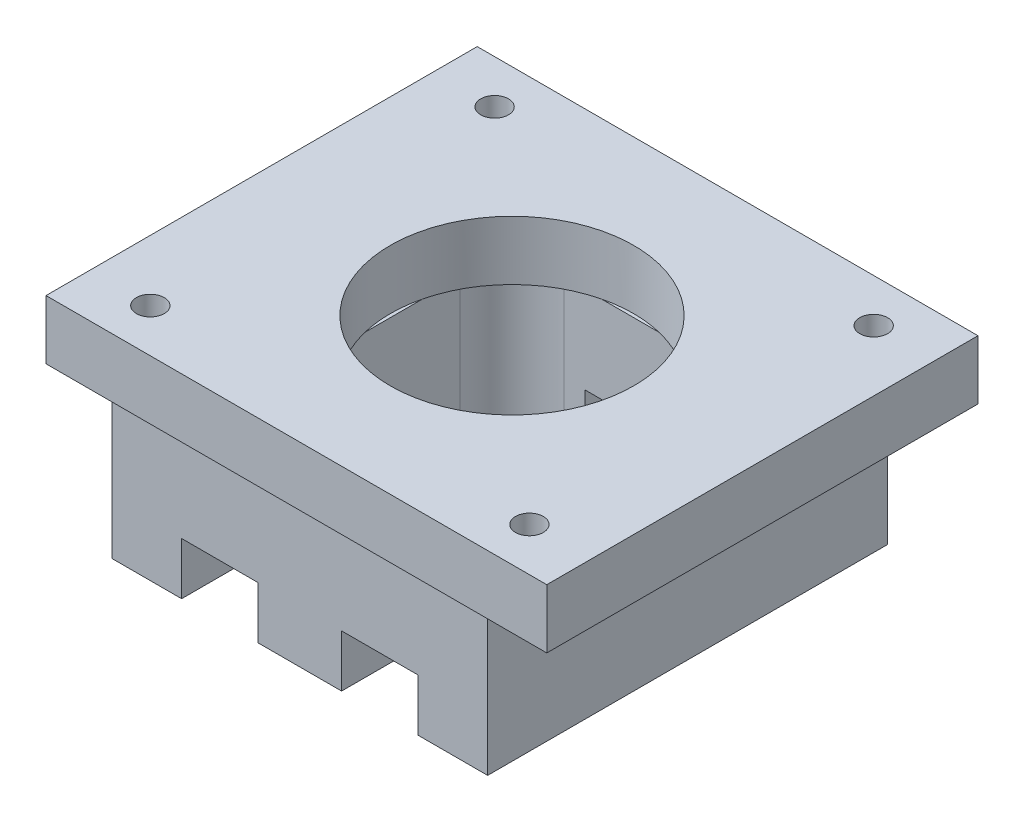
SolidWorks part; units mm, degrees
ref_plane "前视基准面" through (0, 0, 0) normal (0, 0, 1) x (1, 0, 0)
ref_plane "上视基准面" through (0, 0, 0) normal (0, 1, 0) x (1, 0, 0)
ref_plane "右视基准面" through (0, 0, 0) normal (1, 0, 0) x (0, 0, -1)
other "Configuration Table"
sketch "草图1" plane through (0, 0, 0) normal (0, 1, 0) x (1, 0, 0)
  line L7 (-7.2, -6.2) -> (7.2, -6.2)
  line L8 (-7.2, -6.2) -> (-7.2, 6.2)
  line L9 (-7.2, 6.2) -> (7.2, 6.2)
  line L10 (7.2, -6.2) -> (7.2, 6.2)
  circle A0 centre (0, 0) radius 3.5
  circle A1 centre (5.45, -4.95) radius 0.4
  circle A2 centre (-5.45, -4.95) radius 0.4
  circle A3 centre (5.45, 4.95) radius 0.4
  circle A4 centre (-5.45, 4.95) radius 0.4
  point P0 (0, 0)
  point P5 (0, 0)
  point P17 (0, 0)
  point P18 (0, 0)
  point P19 (0, 0)
  point P20 (0, 0)
  point P21 (4.8579, -3.3344)
  point P22 (-5.4, 2.7992)
  point P23 (-5.45, 9.163)
  point P24 (-6.5206, 4.0411)
  dimension "D1" = 7
  dimension "D8" = 0.8
  dimension "D2" = 14.4
  dimension "D3" = 12.4
  dimension "D4" = 6.2
  dimension "D5" = 7.2
  dimension "D6" = 1.75
  dimension "D7" = 1.25
  dimension "D9" = 1.75
  dimension "D10" = 1.25
extrude "凸台-拉伸1" add sketch "草图1" along normal blind 1.7
sketch "草图2" plane through (0, 0, 0) normal (0, -1, 0) x (1, 0, 0)
  line L1 (-3.4, -3.4) -> (3.4, -3.4)
  line L2 (-3.4, -3.4) -> (-3.4, 4.1)
  line L3 (-3.4, 4.1) -> (3.4, 4.1)
  line L4 (3.4, -3.4) -> (3.4, 4.1)
  point P0 (0, 0)
  point P5 (0, 0)
  dimension "D1" = 4.1
  dimension "D2" = 3.4
  dimension "D3" = 3.4
  dimension "D4" = 3.4
extrude "拉伸-薄壁1" add sketch "草图2" along normal blind 4 thin contours L2 L3 L4 L1
fillet "圆角1" radius 1.5 2 edges at (3.4, -2, -3.4) (-3.4, -2, -3.4)
sketch "草图3" plane through (0, -4, 0) normal (0, -1, 0) x (1, 0, 0)
  line L0 (-1.9, -3.4) -> (1.9, -3.4) construction
  line L1 (-1.2, 4.1) -> (-3.4, 4.1)
  line L2 (-1.2, 4.1) -> (-1.2, 6.1)
  line L3 (-1.2, 6.1) -> (-3.4, 6.1)
  line L4 (-3.4, 4.1) -> (-3.4, 6.1)
  line L5 (1.2, 6.1) -> (3.4, 6.1)
  line L6 (1.2, 6.1) -> (1.2, 4.1)
  line L7 (1.2, 4.1) -> (3.4, 4.1)
  line L8 (3.4, 6.1) -> (3.4, 4.1)
  line L9 (-1.3, -3.4) -> (1.3, -3.4)
  line L10 (-1.3, -3.4) -> (-1.3, -5.4)
  line L11 (-1.3, -5.4) -> (1.3, -5.4)
  line L12 (1.3, -3.4) -> (1.3, -5.4)
  line L13 (-5.4, -5.4) -> (5.4, -5.4) construction
  line L14 (-5.4, 6.1) -> (5.4, 6.1) construction
  line L15 (-3.4, 4.1) -> (3.4, 4.1) construction
  line L16 (-3.4, -1.9) -> (-3.4, 4.1) construction
  line L17 (3.4, -1.9) -> (3.4, 4.1) construction
  point P12 (0, 0)
  point P17 (0, 0)
  point P19 (0, 0)
  point P22 (0, 0)
  point P23 (0, 0)
  point P26 (0, 0)
  point P27 (0, 0)
  point P30 (0, 0)
  dimension "D1" = 1.3
  dimension "D2" = 1.3
  dimension "D3" = 1.2
  dimension "D4" = 1.2
extrude "切除-拉伸1" cut sketch "草图3" against normal blind 1.5
sketch "草图4" plane through (0, -4, 0) normal (0, -1, 0) x (1, 0, 0)
  line L0 (-1.2, 6.1) -> (1.2, 6.1) construction
  line L2 (-5.4, -5.4) -> (-1.3, -5.4) construction
  line L3 (-5.4, -5.4) -> (-5.4, 6.1) construction
  line L4 (5.4, -5.4) -> (5.4, 6.1) construction
  circle A0 centre (-3.9, -4.15) radius 0.4
  circle A1 centre (3.9, -4.15) radius 0.4
  circle A3 centre (0, 5.1) radius 0.4
  point P4 (3.9831, -4.0686)
  point P8 (0, 0)
  point P10 (0, 4.7859)
  point P11 (0, 0)
  dimension "D1" = 0.8
  dimension "D2" = 1
  dimension "D3" = 1.25
  dimension "D4" = 1.5
  dimension "D5" = 1.5
extrude "切除-拉伸2" cut sketch "草图4" against normal blind 3 contours A0 | A1 | A3
